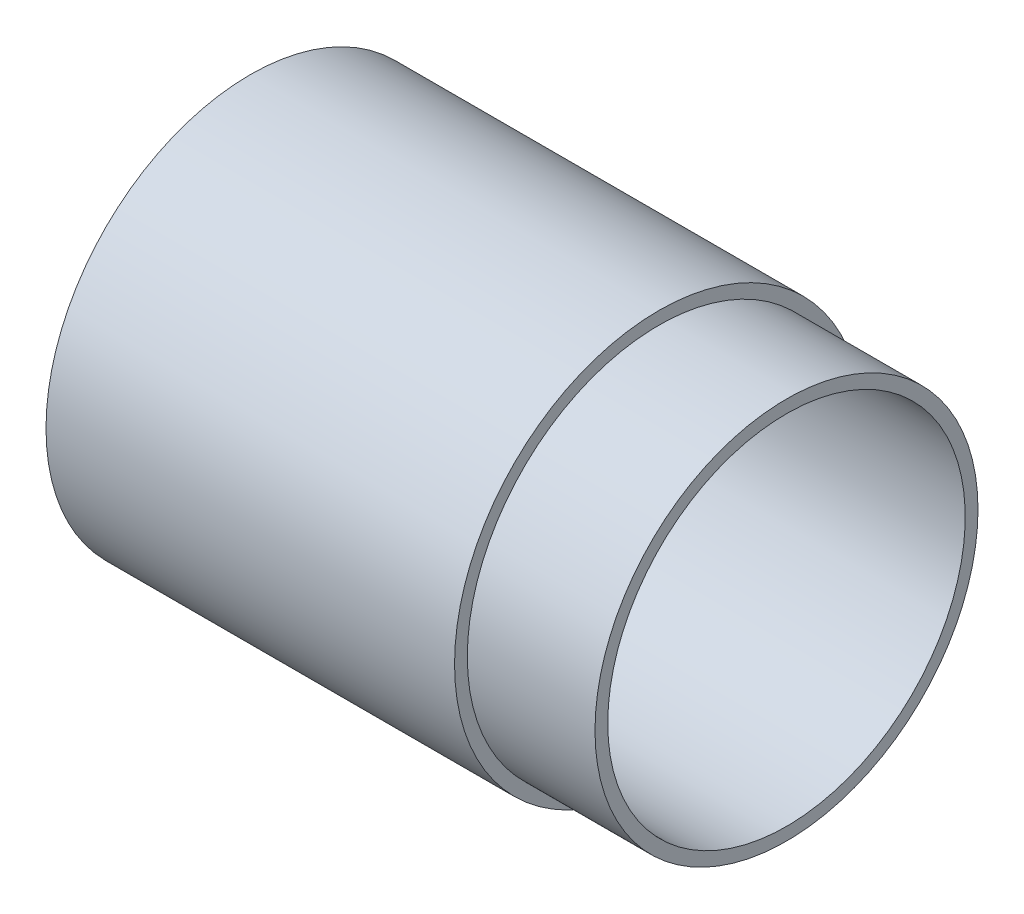
SolidWorks part; units mm, degrees
ref_plane "Ebene vorne" through (0, 0, 0) normal (0, 0, 1) x (1, 0, 0)
ref_plane "Ebene oben" through (0, 0, 0) normal (0, 1, 0) x (1, 0, 0)
ref_plane "Ebene rechts" through (0, 0, 0) normal (1, 0, 0) x (0, 0, -1)
sketch "Skizze1" plane through (0, 0, 0) normal (0, 0, 1) x (1, 0, 0)
  line L0 (0, 0) -> (100, 0) construction
  line L2 (0, 80) -> (160, 80)
  line L3 (0, 80) -> (0, 75)
  line L4 (0, 75) -> (160, 75)
  line L5 (160, 80) -> (160, 75)
  line L6 (0, 80) -> (160, 75) construction
  line L7 (0, 75) -> (160, 80) construction
  line L8 (110, 75) -> (210, 75)
  line L9 (110, 75) -> (110, 70)
  line L10 (110, 70) -> (210, 70)
  line L11 (210, 75) -> (210, 70)
  point P3 (80, 77.5)
  dimension "D1" = 100
  dimension "D2" = 5
  dimension "D3" = 160
  dimension "D4" = 5
  dimension "D5" = 100
  dimension "D6" = 80
  dimension "D7" = 50
revolve "Rotation1" add sketch "Skizze1" angle 360 about L0
